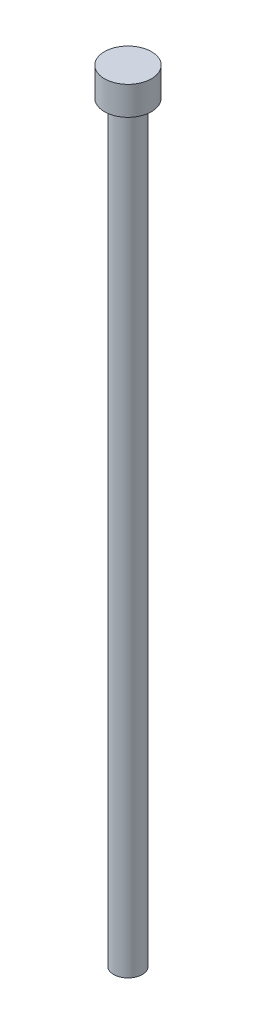
SolidWorks part; units mm, degrees
ref_plane "Front Plane" through (0, 0, 0) normal (0, 0, 1) x (1, 0, 0)
ref_plane "Top Plane" through (0, 0, 0) normal (0, 1, 0) x (1, 0, 0)
ref_plane "Right Plane" through (0, 0, 0) normal (1, 0, 0) x (0, 0, -1)
sketch "Sketch1" plane through (0, 0, 0) normal (0, 1, 0) x (1, 0, 0)
  circle A0 centre (0, 0) radius 3.9688
  dimension "D1" = 7.9375
extrude "Boss-Extrude1" add sketch "Sketch1" along normal blind 4.826
sketch "Sketch2" plane through (0, 0, 0) normal (0, -1, 0) x (1, 0, 0)
  circle A0 centre (0, 0) radius 2.413
  dimension "D1" = 4.826
extrude "Boss-Extrude2" add sketch "Sketch2" along normal blind 127
